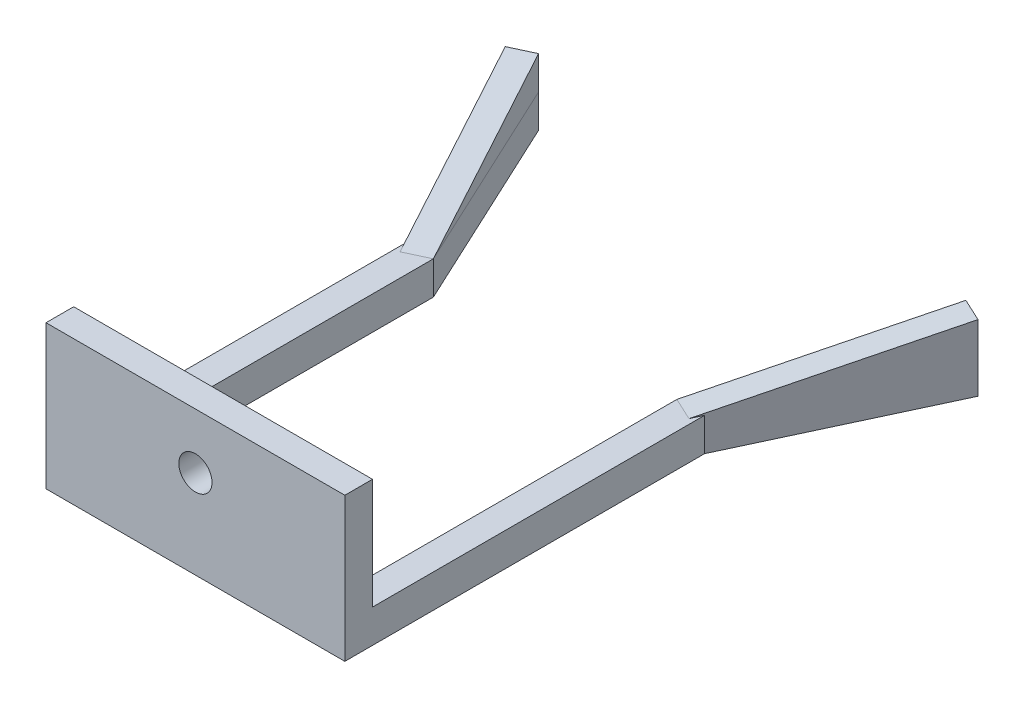
SolidWorks part; units mm, degrees
ref_plane "Front Plane" through (0, 0, 0) normal (0, 0, 1) x (1, 0, 0)
ref_plane "Top Plane" through (0, 0, 0) normal (0, 1, 0) x (1, 0, 0)
ref_plane "Right Plane" through (0, 0, 0) normal (1, 0, 0) x (0, 0, -1)
sketch "Sketch1" plane through (0, 0, 0) normal (0, 1, 0) x (1, 0, 0)
  line L0 (0, -7.15) -> (0, 7.15) construction
  line L6 (-13.5, -2.5) -> (13.5, -2.5)
  line L12 (11, 0) -> (11, 30)
  line L15 (-11, 0) -> (-11, 30)
  line L16 (-11, 0) -> (11, 0)
  line L17 (-13.5, 30) -> (-13.5, -2.5)
  line L18 (13.5, -2.5) -> (13.5, 30)
  line L19 (-11, 30) -> (-19.3036, 47.8071)
  line L20 (-19.3036, 47.8071) -> (-21.3571, 46.8495)
  line L21 (-21.3571, 46.8495) -> (-13.5, 30)
  line L22 (19.3036, 47.8071) -> (21.3571, 46.8495)
  line L23 (21.3571, 46.8495) -> (13.5, 30)
  line L24 (11, 30) -> (19.3036, 47.8071)
  point P0 (0, 0)
  dimension "D1" = 22
  dimension "D2" = 2.5
  dimension "D3" = 2.5
  dimension "D4" = 18.5914
  dimension "D5" = 155
  dimension "D6" = 30
extrude "Boss-Extrude1" add sketch "Sketch1" along normal blind 3
sketch "Sketch2" plane through (2.4553, 0, -1.1449) normal (0.9063, 0, -0.4226) x (-0.4226, 0, -0.9063)
  line L0 (31.838, 3) -> (51.486, 6)
  line L1 (51.486, 6) -> (51.486, 3)
  line L2 (31.838, 3) -> (51.486, 3) construction
  line L3 (31.838, 3) -> (51.486, 3)
  dimension "D1" = 3
extrude "Boss-Extrude2" add sketch "Sketch2" against normal up to surface (2.2658 mm away) separate body up to face at (-17.4285, 1.5, -38.4248)
mirror "Mirror4" about plane through (0, 0, 0) normal (1, 0, 0) of "Boss-Extrude2"
fillet "Fillet1" [suppressed] radius 2
sketch "Sketch3" plane through (0, 3, 0) normal (0, 1, 0) x (1, 0, 0)
  line L0 (13.5, -2.5) -> (13.5, 30) construction
  line L1 (-13.5, -2.5) -> (13.5, -2.5)
  line L2 (-13.5, -2.5) -> (-13.5, 0)
  line L3 (-13.5, 0) -> (13.5, 0)
  line L4 (13.5, -2.5) -> (13.5, 0)
  line L5 (11, 0) -> (-11, 0) construction
extrude "Boss-Extrude3" add sketch "Sketch3" along normal blind 10
sketch "Sketch4" plane through (0, 0, 0) normal (0, 0, -1) x (-1, 0, 0)
  line L0 (13.5, 13) -> (13.5, 3) construction
  circle A0 centre (0, 8) radius 1.5
  point P4 (13.5, 8)
  dimension "D1" = 3
extrude "Cut-Extrude1" cut sketch "Sketch4" against normal through all
